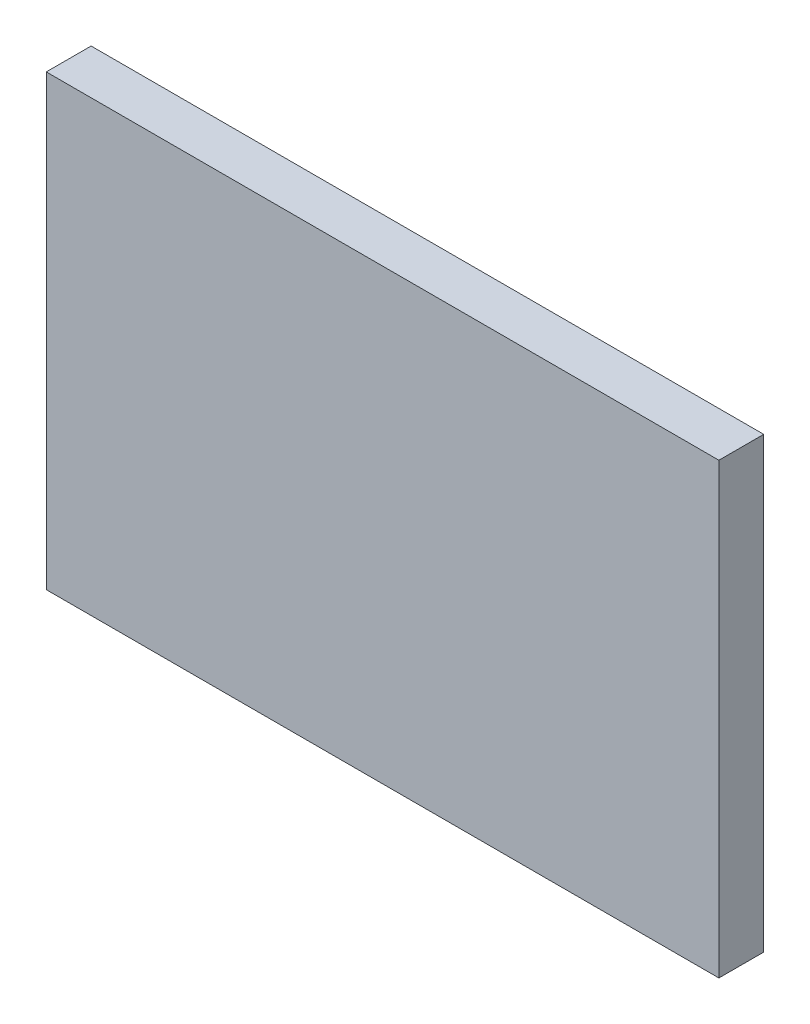
SolidWorks part; units mm, degrees
ref_plane "Front Plane" through (0, 0, 0) normal (0, 0, 1) x (1, 0, 0)
ref_plane "Top Plane" through (0, 0, 0) normal (0, 1, 0) x (1, 0, 0)
ref_plane "Right Plane" through (0, 0, 0) normal (1, 0, 0) x (0, 0, -1)
sketch "Sketch1" plane through (0, 0, 0) normal (0, 0, 1) x (1, 0, 0)
  line L1 (45, -30) -> (-45, -30)
  line L2 (45, -30) -> (45, 30)
  line L3 (45, 30) -> (-45, 30)
  line L4 (-45, -30) -> (-45, 30)
  line L5 (45, -30) -> (-45, 30) construction
  line L6 (45, 30) -> (-45, -30) construction
  point P0 (0, 0)
  dimension "D1" = 90
  dimension "D2" = 60
extrude "Boss-Extrude1" add sketch "Sketch1" along normal blind 6
